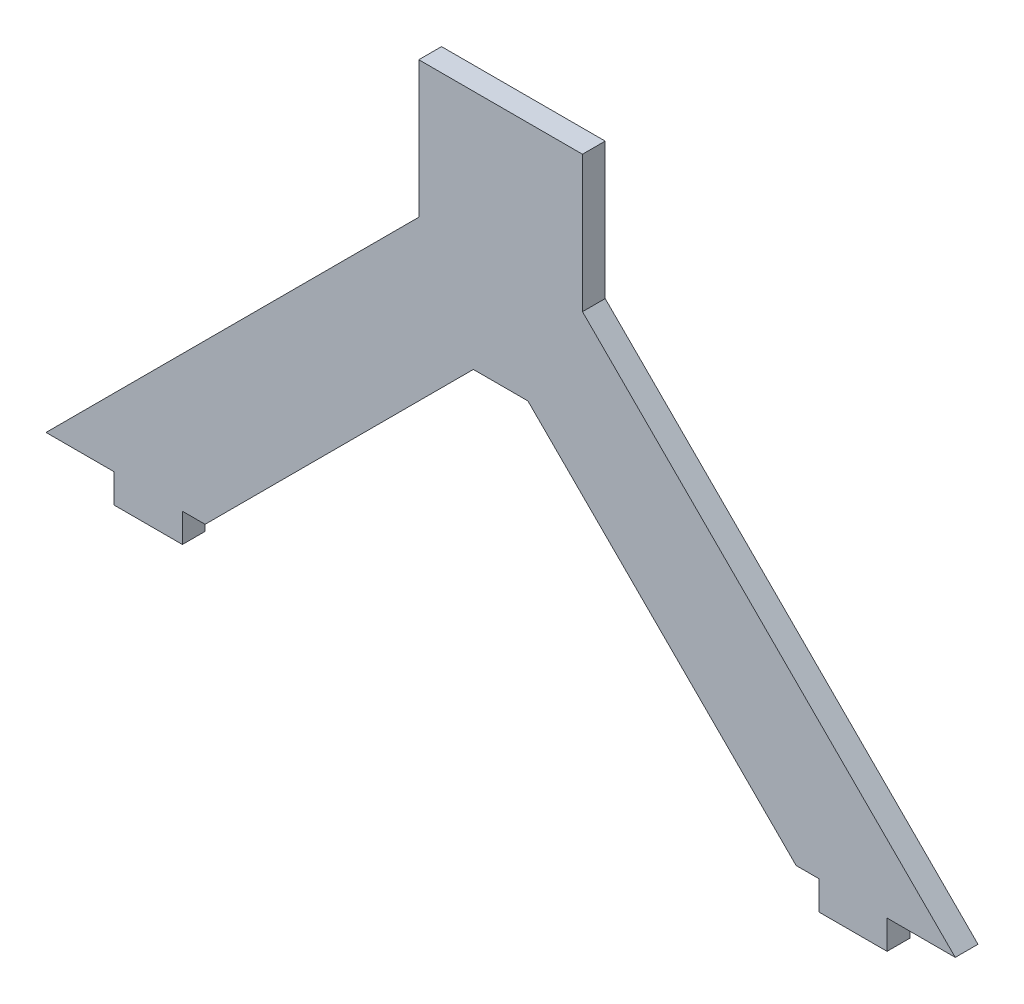
SolidWorks part; units mm, degrees
ref_plane "Front Plane" through (0, 0, 0) normal (0, 0, 1) x (1, 0, 0)
ref_plane "Top Plane" through (0, 0, 0) normal (0, 1, 0) x (1, 0, 0)
ref_plane "Right Plane" through (0, 0, 0) normal (1, 0, 0) x (0, 0, -1)
sketch "Sketch1" plane through (0, 0, 0) normal (0, 0, 1) x (1, 0, 0)
  line L0 (30, 0) -> (15, 0)
  line L1 (15, 0) -> (15, 6.35)
  line L2 (15, 6.35) -> (0, 6.35)
  line L3 (0, 6.35) -> (82, 88.35)
  line L4 (118, 88.35) -> (200, 6.35)
  line L5 (200, 6.35) -> (185, 6.35)
  line L6 (185, 6.35) -> (185, 0)
  line L7 (185, 0) -> (170, 0)
  line L8 (170, 0) -> (170, 6.35)
  line L9 (170, 6.35) -> (165, 6.35)
  line L10 (165, 6.35) -> (106, 65.35)
  line L11 (94, 65.35) -> (35, 6.35)
  line L12 (35, 6.35) -> (30, 6.35)
  line L13 (30, 6.35) -> (30, 0)
  line L14 (94, 65.35) -> (106, 65.35)
  line L15 (118, 88.35) -> (118, 118.35)
  line L16 (118, 118.35) -> (82, 118.35)
  line L17 (82, 118.35) -> (82, 88.35)
  line L18 (100, -893.65) -> (100, 49106.35) construction
  dimension "D1" = 5
  dimension "D2" = 5
  dimension "D3" = 12
  dimension "D4" = 59
  dimension "D5" = 30
  dimension "D6" = 36
  dimension "D7" = 82
extrude "Boss-Extrude1" add sketch "Sketch1" along normal blind 5
